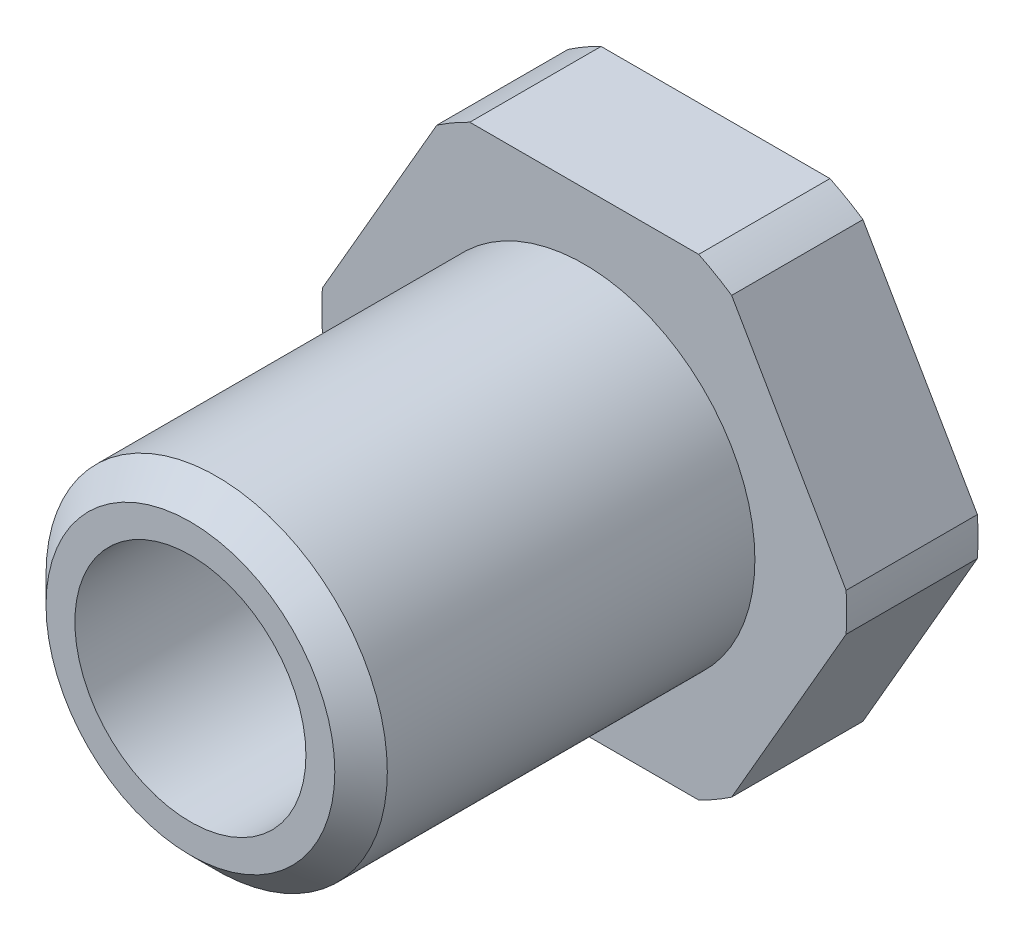
SolidWorks part; units mm, degrees
ref_plane "前视基准面" through (0, 0, 0) normal (0, 0, 1) x (1, 0, 0)
ref_plane "上视基准面" through (0, 0, 0) normal (0, 1, 0) x (1, 0, 0)
ref_plane "右视基准面" through (0, 0, 0) normal (1, 0, 0) x (0, 0, -1)
sketch "草图1" plane through (0, 0, 0) normal (0, 0, 1) x (1, 0, 0)
  line L1 (10.3923, 0) -> (5.1962, 9)
  line L2 (5.1962, 9) -> (-5.1962, 9)
  line L3 (-5.1962, 9) -> (-10.3923, 0)
  line L4 (-10.3923, 0) -> (-5.1962, -9)
  line L5 (-5.1962, -9) -> (5.1962, -9)
  line L6 (5.1962, -9) -> (10.3923, 0)
  circle A0 centre (0, 0) radius 9 construction
  dimension "D1" = 18
extrude "凸台-拉伸1" add sketch "草图1" along normal blind 5
sketch "草图2" plane through (0, 0, 5) normal (0, 0, 1) x (1, 0, 0)
  circle A0 centre (0, 0) radius 6.5
  dimension "D1" = 13
extrude "凸台-拉伸2" add sketch "草图2" along normal blind 15
sketch "草图5" plane through (0, 0, 5) normal (0, 0, 1) x (1, 0, 0)
  circle A0 centre (0, 0) radius 10
  dimension "D1" = 20
extrude "切除-拉伸1" cut sketch "草图5" against normal through all flip side to cut
chamfer "倒角1" distance 1 angle 45 1 edges at (6.5, 0, 20)
hole_wizard "M10x1.25 螺纹孔1" positions "草图7" profile "草图6" tap size "M10x1.25" standard "JIS" end condition through all
sketch "草图7" plane through (0, 0, 20) normal (0, 0, 1) x (1, 0, 0)
  point P0 (0, 0)
cosmetic thread "孔螺蚊线2" parameters "D2"=10
sketch "草图6" plane through (0, 0, 20) normal (1, 0, 0) x (0, -1, 0)
  line L0 (0, 0) -> (0, 20)
  line L1 (0, 20) -> (4.4, 20)
  line L2 (4.4, 20) -> (4.4, 0)
  line L5 (4.4, 0) -> (0, 0)
  line L11 (0, -6.35) -> (0, 107.95) construction
  dimension "通孔螺纹孔钻头直径" = 8.8
  dimension "通孔螺纹孔钻头深度" = 20
